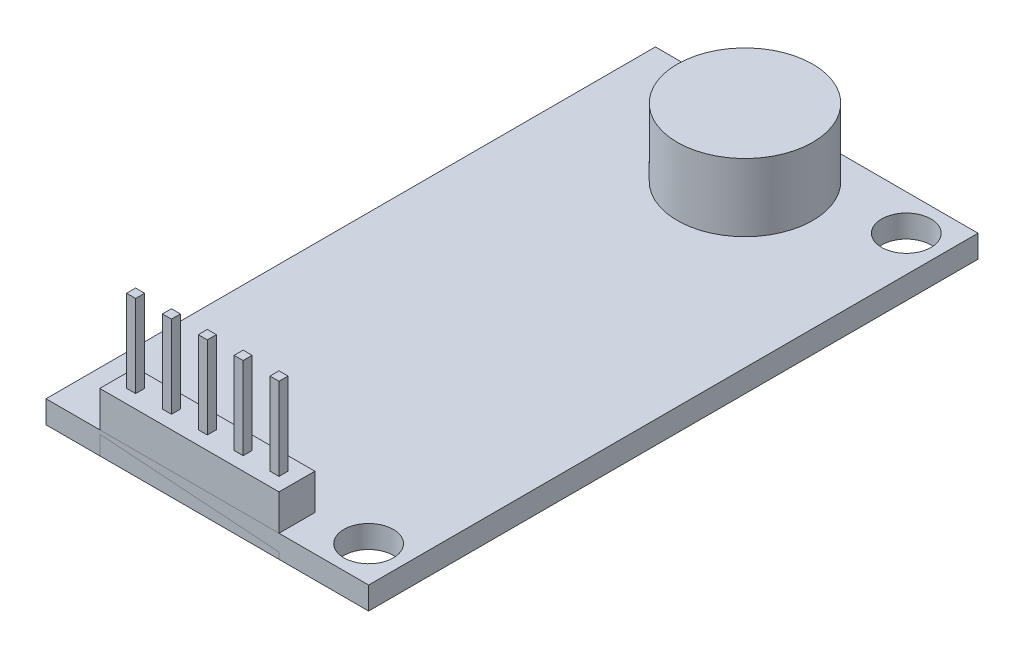
SolidWorks part; units mm, degrees
ref_plane "Front Plane" through (0, 0, 0) normal (0, 0, 1) x (1, 0, 0)
ref_plane "Top Plane" through (0, 0, 0) normal (0, 1, 0) x (1, 0, 0)
ref_plane "Right Plane" through (0, 0, 0) normal (1, 0, 0) x (0, 0, -1)
sketch "Sketch1" plane through (0, 0, 0) normal (0, 1, 0) x (1, 0, 0)
  line L1 (-11.43, -21.59) -> (11.43, -21.59)
  line L2 (-11.43, -21.59) -> (-11.43, 21.59)
  line L3 (-11.43, 21.59) -> (11.43, 21.59)
  line L4 (11.43, -21.59) -> (11.43, 21.59)
  line L5 (-11.43, -21.59) -> (11.43, 21.59) construction
  line L6 (-11.43, 21.59) -> (11.43, -21.59) construction
  point P0 (0, 0)
  dimension "D1" = 43.18
  dimension "D2" = 22.86
extrude "Boss-Extrude1" add sketch "Sketch1" along normal blind 1.6
sketch "Sketch2" plane through (0, 1.6, 0) normal (0, 1, 0) x (1, 0, 0)
  line L0 (-11.43, -20.32) -> (11.43, -20.32) construction
  line L1 (-11.43, 21.59) -> (-11.43, -21.59) construction
  line L2 (11.43, -21.59) -> (11.43, 21.59) construction
  line L3 (-11.43, -21.59) -> (11.43, -21.59) construction
  line L4 (-4.13, -20.64) -> (-4.13, -20)
  line L5 (-6.67, -20.64) -> (-6.03, -20.64)
  line L6 (-6.67, -20.64) -> (-6.67, -20)
  line L7 (-6.67, -20) -> (-6.03, -20)
  line L8 (-6.03, -20.64) -> (-6.03, -20)
  line L9 (-6.67, -20.64) -> (-6.03, -20) construction
  line L10 (-6.67, -20) -> (-6.03, -20.64) construction
  line L11 (-4.13, -20.64) -> (-3.49, -20.64)
  line L12 (-3.49, -20.64) -> (-3.49, -20)
  line L13 (-4.13, -20) -> (-3.49, -20)
  line L14 (-1.59, -20.64) -> (-1.59, -20)
  line L15 (-1.59, -20.64) -> (-0.95, -20.64)
  line L16 (-0.95, -20.64) -> (-0.95, -20)
  line L17 (-1.59, -20) -> (-0.95, -20)
  line L18 (0.95, -20.64) -> (0.95, -20)
  line L19 (0.95, -20.64) -> (1.59, -20.64)
  line L20 (1.59, -20.64) -> (1.59, -20)
  line L21 (0.95, -20) -> (1.59, -20)
  line L22 (3.49, -20.64) -> (3.49, -20)
  line L23 (3.49, -20.64) -> (4.13, -20.64)
  line L24 (4.13, -20.64) -> (4.13, -20)
  line L25 (3.49, -20) -> (4.13, -20)
  point P8 (-6.35, -20.32)
  dimension "D1" = 1.27
  dimension "D2" = 0.64
  dimension "D3" = 5.08
  dimension "D4" = 5
extrude "Boss-Extrude2" add sketch "Sketch2" along normal blind 8.38
sketch "Sketch3" plane through (0, 1.6, 0) normal (0, 1, 0) x (1, 0, 0)
  line L0 (11.43, 21.59) -> (-11.43, 21.59) construction
  line L1 (11.43, -21.59) -> (11.43, 21.59) construction
  line L2 (0, 0) -> (11.43, 0) construction
  circle A0 centre (8.89, 19.05) radius 1.75
  circle A1 centre (8.89, -19.05) radius 1.75
  dimension "D1" = 3.5
  dimension "D2" = 2.54
  dimension "D3" = 2.54
extrude "Cut-Extrude1" cut sketch "Sketch3" against normal up to surface (1.6 mm away) up to face at (0, 0, 0)
sketch "Sketch4" plane through (0, 1.6, 0) normal (0, 1, 0) x (1, 0, 0)
  line L0 (11.43, 21.59) -> (-11.43, 21.59) construction
  line L1 (-11.43, 21.59) -> (-11.43, -21.59) construction
  circle A0 centre (0, 16.51) radius 4.8
  dimension "D1" = 9.6
  dimension "D2" = 5.08
  dimension "D3" = 11.43
extrude "Boss-Extrude3" add sketch "Sketch4" along normal blind 4.8
sketch "Sketch5" plane through (0, 0, 0) normal (0, -1, 0) x (1, 0, 0)
  line L0 (-1.59, 20.32) -> (-0.95, 20.32) construction
  line L1 (-7.62, 21.59) -> (5.08, 21.59)
  line L2 (-7.62, 21.59) -> (-7.62, 19.05)
  line L3 (-7.62, 19.05) -> (5.08, 19.05)
  line L4 (5.08, 21.59) -> (5.08, 19.05)
  line L5 (-7.62, 21.59) -> (5.08, 19.05) construction
  line L6 (-7.62, 19.05) -> (5.08, 21.59) construction
  line L7 (-1.27, 20.64) -> (-1.27, 20) construction
  line L10 (-1.59, 20) -> (-0.95, 20)
  line L11 (-0.95, 20) -> (-0.95, 20.64)
  line L12 (-0.95, 20.64) -> (-1.59, 20.64)
  line L13 (-1.59, 20.64) -> (-1.59, 20)
  line L14 (-1.59, 20) -> (-0.95, 20)
  line L15 (-0.95, 20) -> (-0.95, 20.64)
  line L16 (-0.95, 20.64) -> (-1.59, 20.64)
  line L17 (-1.59, 20.64) -> (-1.59, 20)
  point P0 (-1.27, 20.32)
  point P13 (0, 0)
  point P14 (-1.27, 20.32)
  point P15 (0, 0)
  dimension "D1" = 2.54
  dimension "D2" = 12.7
  dimension "D3" = 0
extrude "Boss-Extrude4" add sketch "Sketch5" against normal blind 4.14 separate body
